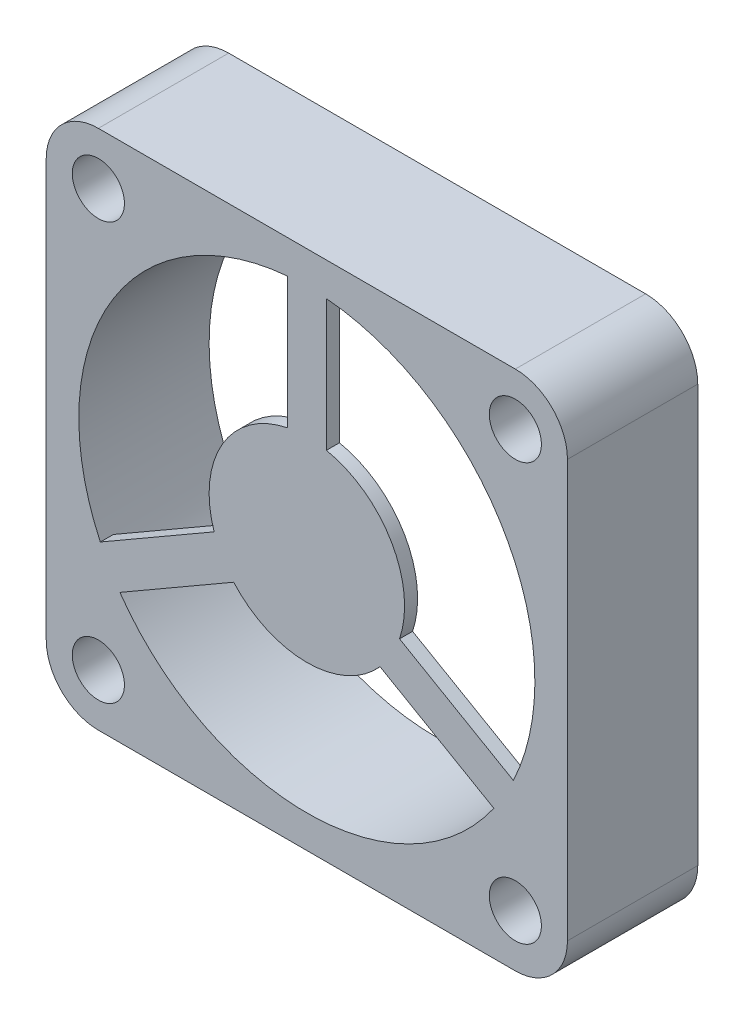
SolidWorks part; units mm, degrees
ref_plane "前视基准面" through (0, 0, 0) normal (0, 0, 1) x (1, 0, 0)
ref_plane "上视基准面" through (0, 0, 0) normal (0, 1, 0) x (1, 0, 0)
ref_plane "右视基准面" through (0, 0, 0) normal (1, 0, 0) x (0, 0, -1)
sketch "草图1" plane through (0, 0, 0) normal (0, 0, 1) x (1, 0, 0)
  line L1 (-16, -20) -> (16, -20)
  line L2 (-20, -16) -> (-20, 16)
  line L3 (-16, 20) -> (16, 20)
  line L4 (20, -16) -> (20, 16)
  line L5 (-20, -20) -> (20, 20) construction
  line L6 (-20, 20) -> (20, -20) construction
  line L7 (16, -16) -> (-16, -16) construction
  line L8 (16, -16) -> (16, 16) construction
  line L9 (16, 16) -> (-16, 16) construction
  line L10 (-16, -16) -> (-16, 16) construction
  line L11 (16, -16) -> (-16, 16) construction
  line L12 (16, 16) -> (-16, -16) construction
  circle A0 centre (0, 0) radius 17.5
  circle A1 centre (-16, 16) radius 2
  circle A2 centre (16, 16) radius 2
  circle A3 centre (16, -16) radius 2
  circle A4 centre (-16, -16) radius 2
  arc A5 (-16, -20) -> (-20, -16) centre (-16, -16) cw
  arc A6 (16, -20) -> (20, -16) centre (16, -16) ccw
  arc A7 (16, 20) -> (20, 16) centre (16, 16) cw
  arc A8 (-20, 16) -> (-16, 20) centre (-16, 16) cw
  point P0 (0, 0)
  dimension "D2" = 35
  dimension "D4" = 4
  dimension "D5" = 4
  dimension "D1" = 40
  dimension "D3" = 32
extrude "凸台-拉伸1" add sketch "草图1" along normal blind 10
sketch "草图2" plane through (0, 0, 10) normal (0, 0, 1) x (1, 0, 0)
  line L0 (-1.5, 17.4356) -> (-1.5, 7.3485)
  line L1 (1.5, 7.3485) -> (1.5, 17.4356)
  line L2 (0, 7.5) -> (0, 25.9936) construction
  line L3 (15.8497, -7.4188) -> (7.114, -2.3752)
  line L4 (5.614, -4.9733) -> (14.3497, -10.0168)
  line L5 (-14.3497, -10.0168) -> (-5.614, -4.9733)
  line L6 (-7.114, -2.3752) -> (-15.8497, -7.4188)
  arc A0 (-1.5, 7.3485) -> (-7.114, -2.3752) centre (0, 0) ccw
  circle A2 centre (0, 0) radius 17.5 construction
  arc A3 (-14.3497, -10.0168) -> (-15.8497, -7.4188) centre (0, 0) cw
  arc A4 (14.3497, -10.0168) -> (15.8497, -7.4188) centre (0, 0) ccw
  arc A5 (-1.5, 17.4356) -> (1.5, 17.4356) centre (0, 0) cw
  arc A6 (7.114, -2.3752) -> (1.5, 7.3485) centre (0, 0) ccw
  arc A7 (-5.614, -4.9733) -> (5.614, -4.9733) centre (0, 0) ccw
  point P22 (0, 0)
  dimension "D1" = 15
  dimension "D2" = 1.5
  dimension "D3" = 1.5
  dimension "D4" = 3
extrude "凸台-拉伸2" add sketch "草图2" against normal blind 1
